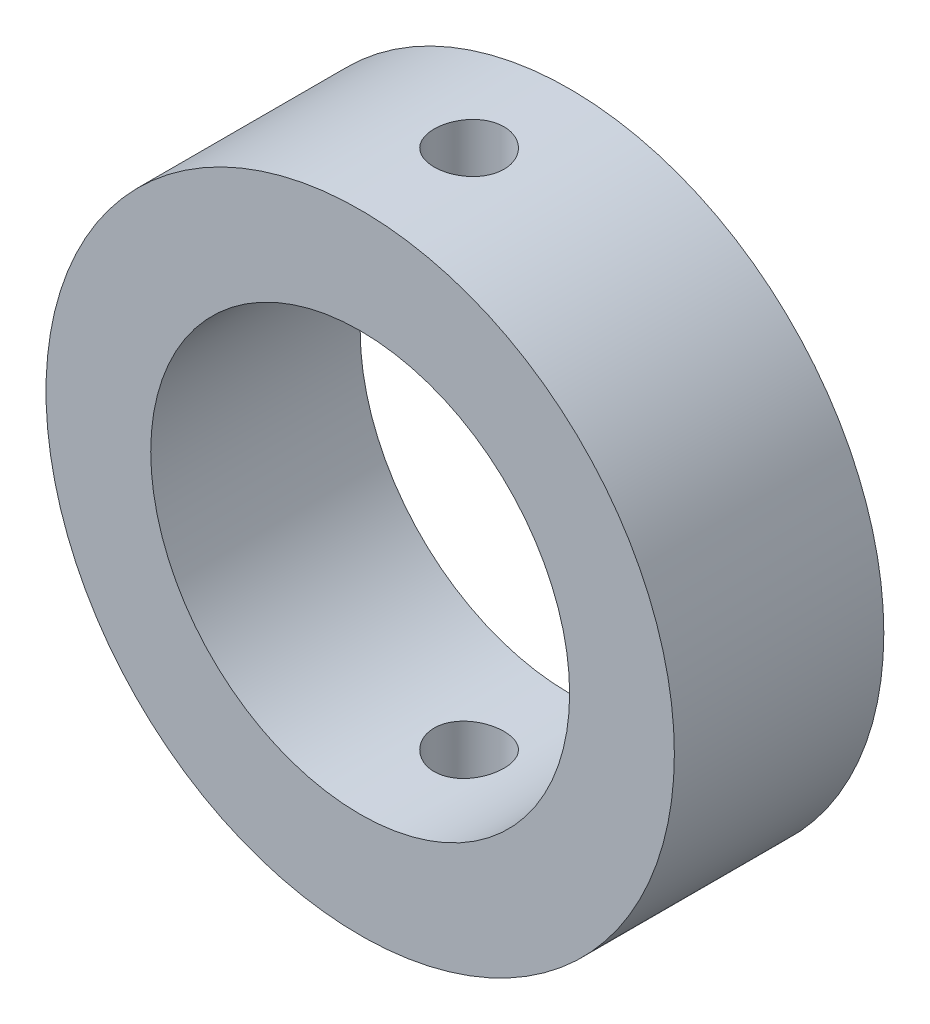
SolidWorks part; units mm, degrees
ref_plane "Front Plane" through (0, 0, 0) normal (0, 0, 1) x (1, 0, 0)
ref_plane "Top Plane" through (0, 0, 0) normal (0, 1, 0) x (1, 0, 0)
ref_plane "Right Plane" through (0, 0, 0) normal (1, 0, 0) x (0, 0, -1)
sketch "Sketch2" plane through (0, 0, 0) normal (0, 0, 1) x (1, 0, 0)
  circle A0 centre (0, 0) radius 22.5
  circle A1 centre (0, 0) radius 15
extrude "Boss-Extrude1" add sketch "Sketch2" along normal blind 15
sketch "Sketch3" plane through (0, 0, 0) normal (0, 1, 0) x (1, 0, 0)
  circle A0 centre (0, -7.2015) radius 2.5
  dimension "D1" = 5
extrude "Cut-Extrude1" cut sketch "Sketch3" against normal mid plane 100
